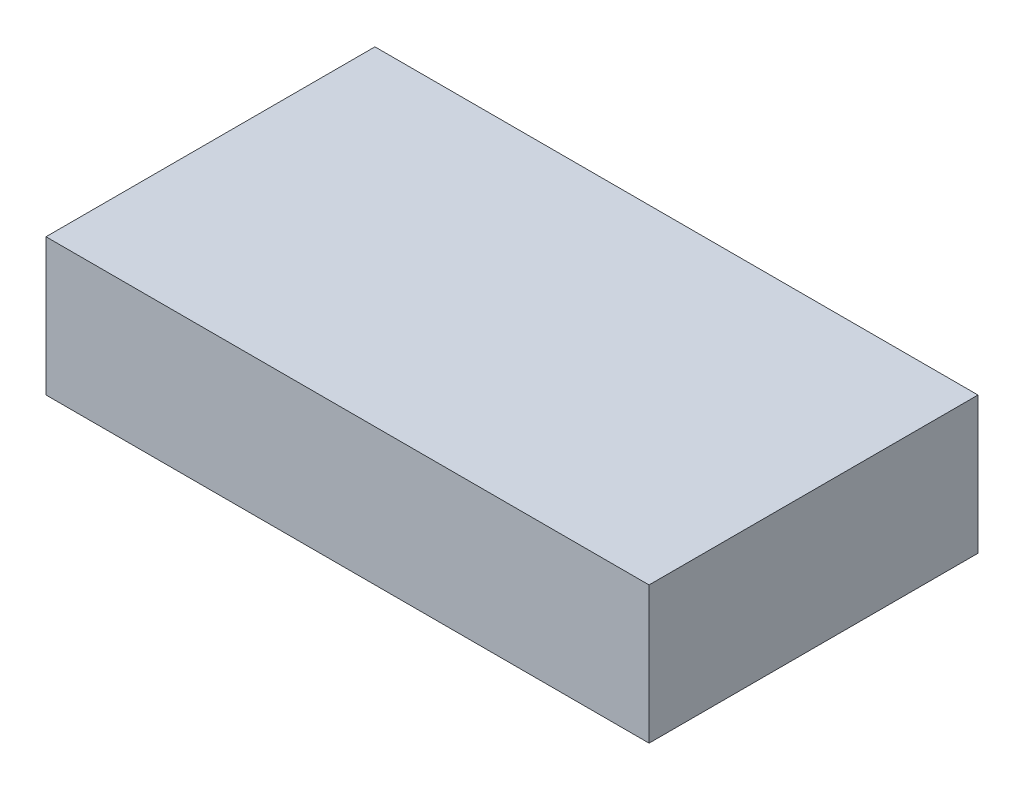
SolidWorks part; units mm, degrees
ref_plane "前视基准面" through (0, 0, 0) normal (0, 0, 1) x (1, 0, 0)
ref_plane "上视基准面" through (0, 0, 0) normal (0, 1, 0) x (1, 0, 0)
ref_plane "右视基准面" through (0, 0, 0) normal (1, 0, 0) x (0, 0, -1)
sketch "草图2" plane through (0, 0, 0) normal (0, 1, 0) x (1, 0, 0)
  line L1 (-49.5261, -50.1237) -> (-27.5261, -50.1237)
  line L2 (-49.5261, -50.1237) -> (-49.5261, -62.1237)
  line L3 (-49.5261, -62.1237) -> (-27.5261, -62.1237)
  line L4 (-27.5261, -50.1237) -> (-27.5261, -62.1237)
extrude "凸台-拉伸1" add sketch "草图2" along normal blind 5
